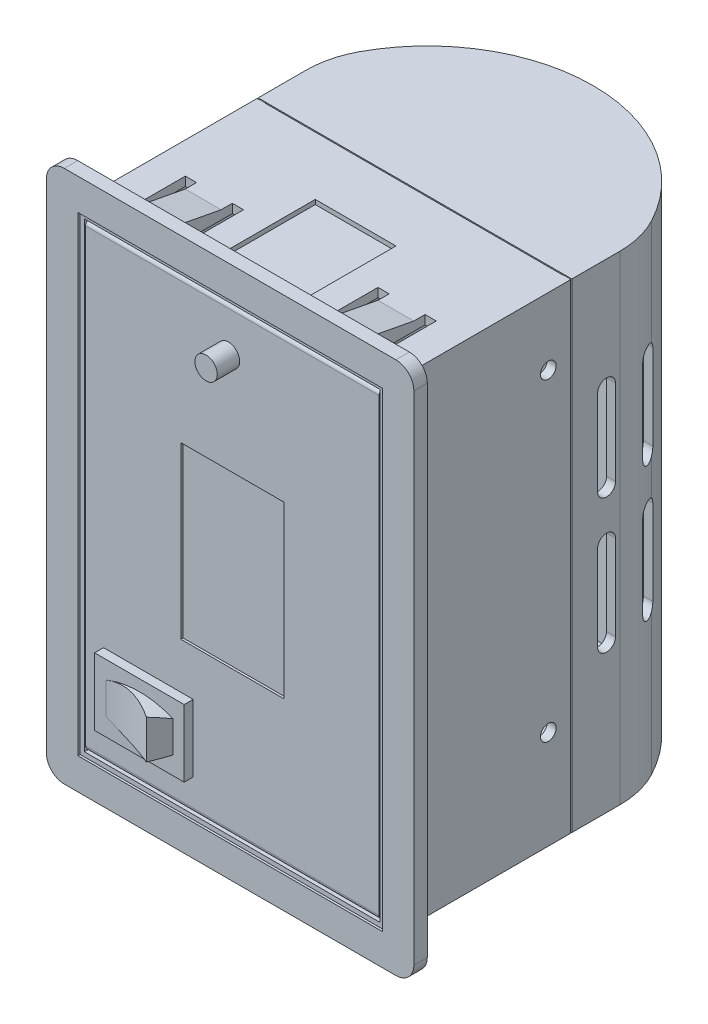
SolidWorks part; units mm, degrees
ref_plane "Спереди" through (0, 0, 0) normal (0, 0, 1) x (1, 0, 0)
ref_plane "Сверху" through (0, 0, 0) normal (0, 1, 0) x (1, 0, 0)
ref_plane "Справа" through (0, 0, 0) normal (1, 0, 0) x (0, 0, -1)
sketch "Эскиз1" plane through (0, 0, 0) normal (0, 0, 1) x (1, 0, 0)
  line L1 (-33, -51.5) -> (33, -51.5)
  line L2 (-33, -51.5) -> (-33, 51.5)
  line L3 (-33, 51.5) -> (33, 51.5)
  line L4 (33, -51.5) -> (33, 51.5)
  line L5 (-33, -51.5) -> (33, 51.5) construction
  line L6 (-33, 51.5) -> (33, -51.5) construction
  line L7 (-35, -53.5) -> (35, -53.5)
  line L8 (-35, -53.5) -> (-35, 53.5)
  line L9 (-35, 53.5) -> (35, 53.5)
  line L10 (35, -53.5) -> (35, 53.5)
  line L11 (-35, -53.5) -> (35, 53.5) construction
  line L12 (-35, 53.5) -> (35, -53.5) construction
  point P0 (0, 0)
  point P6 (0, 0)
  dimension "D1" = 2
  dimension "D2" = 2
  dimension "D3" = 107
  dimension "D4" = 70
extrude "Бобышка-Вытянуть1" add sketch "Эскиз1" along normal blind 38
sketch "Эскиз2" plane through (0, 0, 38) normal (0, 0, 1) x (1, 0, 0)
  line L1 (-37, -59.5) -> (37, -59.5)
  line L2 (-41, -55.5) -> (-41, 55.5)
  line L3 (-37, 59.5) -> (37, 59.5)
  line L4 (41, -55.5) -> (41, 55.5)
  line L5 (-41, -59.5) -> (41, 59.5) construction
  line L6 (-41, 59.5) -> (41, -59.5) construction
  line L9 (-33, -51.5) -> (33, -51.5)
  line L10 (-33, -51.5) -> (-33, 51.5)
  line L11 (-33, 51.5) -> (33, 51.5)
  line L12 (33, -51.5) -> (33, 51.5)
  line L13 (-33, -51.5) -> (33, 51.5) construction
  line L14 (-33, 51.5) -> (33, -51.5) construction
  arc A0 (-41, -55.5) -> (-37, -59.5) centre (-37, -55.5) ccw
  arc A1 (41, -55.5) -> (37, -59.5) centre (37, -55.5) cw
  arc A2 (41, 55.5) -> (37, 59.5) centre (37, 55.5) ccw
  arc A3 (-41, 55.5) -> (-37, 59.5) centre (-37, 55.5) cw
  point P0 (0, 0)
  point P6 (0, 0)
  dimension "D3" = 4
  dimension "D1" = 82
  dimension "D2" = 119
extrude "Бобышка-Вытянуть2" add sketch "Эскиз2" along normal blind 3
sketch "Эскиз3" plane through (0, 0, 41) normal (0, 0, 1) x (1, 0, 0)
  line L0 (33, -51.5) -> (33, 51.5) construction
  line L1 (-34, -52.5) -> (34, -52.5)
  line L2 (-34, -52.5) -> (-34, 52.5)
  line L3 (-34, 52.5) -> (34, 52.5)
  line L4 (34, -52.5) -> (34, 52.5)
  line L5 (-34, -52.5) -> (34, 52.5) construction
  line L6 (-34, 52.5) -> (34, -52.5) construction
  line L7 (33, 51.5) -> (-33, 51.5) construction
  point P0 (0, 0)
  dimension "D1" = 1
  dimension "D2" = 1
extrude "Вырез-Вытянуть1" cut sketch "Эскиз3" against normal blind 0.5
sketch "Эскиз4" plane through (0, 53.5, 0) normal (0, 1, 0) x (1, 0, 0)
  line L0 (37, -38) -> (-37, -38) construction
  line L1 (-9, -13) -> (9, -13)
  line L2 (-9, -13) -> (-9, -38)
  line L3 (-9, -38) -> (9, -38)
  line L4 (9, -13) -> (9, -38)
  line L5 (-9, -13) -> (9, -38) construction
  line L6 (-9, -38) -> (9, -13) construction
  point P0 (0, -25.5)
  dimension "D1" = 25
  dimension "D2" = 18
extrude "Вырез-Вытянуть2" cut sketch "Эскиз4" against normal blind 1
sketch "Эскиз5" plane through (0, 51.5, 0) normal (0, -1, 0) x (1, 0, 0)
  line L1 (33, 0) -> (-33, 0) construction
  line L2 (-10.5, 11) -> (10.5, 11)
  line L3 (-10.5, 11) -> (-10.5, 36)
  line L4 (-8.5, 38) -> (8.5, 38)
  line L5 (10.5, 11) -> (10.5, 36)
  line L6 (-10.5, 11) -> (10.5, 38) construction
  line L8 (-10.5, 38) -> (10.5, 11) construction
  arc A0 (10.5, 36) -> (8.5, 38) centre (8.5, 36) ccw
  arc A1 (-8.5, 38) -> (-10.5, 36) centre (-8.5, 36) ccw
  point P0 (0, 24.5)
  dimension "D4" = 2
  dimension "D1" = 27
  dimension "D2" = 21
  dimension "D3" = 11
extrude "Бобышка-Вытянуть3" add sketch "Эскиз5" along normal blind 1
mirror "Зеркальное отражение1" about plane through (0, 0, 0) normal (0, 1, 0) of "Бобышка-Вытянуть3", "Вырез-Вытянуть2"
sketch "Эскиз6" plane through (-35, 0, 0) normal (-1, 0, 0) x (0, 0, 1)
  line L0 (38, -53.5) -> (0, -53.5) construction
  line L1 (0, 53.5) -> (0, -53.5) construction
  line L2 (5, -31.5) -> (5, 38.5) construction
  circle A0 centre (5, -31.5) radius 1.75
  circle A1 centre (5, 38.5) radius 1.75
  dimension "D1" = 22
  dimension "D2" = 3.5
  dimension "D3" = 5
  dimension "D4" = 70
extrude "Вырез-Вытянуть3" cut sketch "Эскиз6" against normal up to surface (70 mm away) up to face at (35, 0, 19)
ref_plane "Плоскость2" through (-32.75, 0, 0) normal (1, 0, 0) x (0, 0, -1)
sketch "Эскиз9" plane through (-32.75, 0, 0) normal (1, 0, 0) x (0, 0, -1)
  line L0 (-38.5, -51.25) -> (-38.5, 51.25)
  line L1 (-38.5, 51.25) -> (-39.5, 51.25)
  line L2 (-40.5, 50.25) -> (-40.5, -50.25)
  line L3 (-39.5, -51.25) -> (-38.5, -51.25)
  line L4 (-40.5, -51.5) -> (0, -51.5) construction
  line L5 (-40.5, -51.5) -> (-40.5, 51.5) construction
  line L6 (-40.5, 51.5) -> (0, 51.5) construction
  arc A0 (-40.5, 50.25) -> (-39.5, 51.25) centre (-39.5, 50.25) cw
  arc A1 (-40.5, -50.25) -> (-39.5, -51.25) centre (-39.5, -50.25) ccw
  point P14 (-40.5, -51.25)
  dimension "D5" = 1
  dimension "D1" = 0.25
  dimension "D2" = 2
  dimension "D3" = 0
  dimension "D4" = 0.25
extrude "Бобышка-Вытянуть4" add sketch "Эскиз9" along normal blind 65.5 separate body
sketch "Эскиз10" plane through (0, 0, 40.5) normal (0, 0, 1) x (1, 0, 0)
  line L0 (-32.75, 50.25) -> (-32.75, -50.25) construction
  line L1 (-28.75, -44.25) -> (-8.75, -44.25)
  line L2 (-28.75, -44.25) -> (-28.75, -29.25)
  line L3 (-28.75, -29.25) -> (-8.75, -29.25)
  line L4 (-8.75, -44.25) -> (-8.75, -29.25)
  line L5 (32.75, -51.25) -> (-32.75, -51.25) construction
  dimension "D1" = 4
  dimension "D2" = 7
  dimension "D3" = 15
  dimension "D4" = 20
extrude "Бобышка-Вытянуть5" add sketch "Эскиз10" along normal blind 2
sketch "Эскиз11" plane through (0, 0, 42.5) normal (0, 0, 1) x (1, 0, 0)
  line L0 (-18.75, -29.25) -> (-18.75, -44.25) construction
  line L1 (-8.75, -29.25) -> (-28.75, -29.25) construction
  line L2 (-28.75, -44.25) -> (-8.75, -44.25) construction
  line L4 (-28.75, -29.25) -> (-28.75, -44.25) construction
  line L5 (-28.75, -36.75) -> (-8.75, -36.75) construction
  line L6 (-8.75, -44.25) -> (-8.75, -29.25) construction
  line L8 (-26.25, -40.25) -> (-26.25, -33.25)
  line L10 (-11.25, -40.25) -> (-11.25, -33.25)
  line L11 (-26.25, -41.75) -> (-11.25, -31.75) construction
  line L12 (-26.25, -31.75) -> (-11.25, -41.75) construction
  arc A0 (-26.25, -33.25) -> (-11.25, -33.25) centre (-18.75, -51.25) cw
  arc A1 (-26.25, -40.25) -> (-11.25, -40.25) centre (-18.75, -22.25) ccw
  point P6 (-18.75, -36.75)
  dimension "D1" = 15
  dimension "D2" = 10
  dimension "D3" = 3.5
  dimension "D4" = 3.5
  dimension "D5" = 3.5
  dimension "D6" = 3.5
extrude "Бобышка-Вытянуть6" add sketch "Эскиз11" along normal blind 3.5
sketch "Эскиз12" plane through (0, -44.25, 0) normal (0, -1, 0) x (1, 0, 0)
  line L1 (-11.25, 46) -> (-26.25, 46) construction
  line L3 (-26.25, 42.5) -> (-26.25, 46)
  line L4 (-26.25, 46) -> (-13.7007, 46)
  arc A0 (-26.25, 42.5) -> (-13.7007, 46) centre (-26.5065, 67.6673) ccw
extrude "Вырез-Вытянуть4" cut sketch "Эскиз12" against normal blind 15
sketch "Эскиз13" plane through (0, -44.25, 0) normal (0, -1, 0) x (1, 0, 0)
  line L0 (-13.7007, 46) -> (-11.25, 42.5)
  line L1 (-11.25, 42.5) -> (-11.25, 46)
  line L2 (-11.25, 46) -> (-13.7007, 46)
extrude "Вырез-Вытянуть5" cut sketch "Эскиз13" against normal blind 15
sketch "Эскиз14" plane through (0, 0, 40.5) normal (0, 0, 1) x (1, 0, 0)
  line L0 (0, 0) -> (-0.8653, 41.25) construction
  line L1 (32.75, 51.25) -> (-32.75, 51.25) construction
  circle A0 centre (-0.8653, 41.25) radius 2.5
  dimension "D2" = 5
  dimension "D1" = 10
extrude "Бобышка-Вытянуть7" add sketch "Эскиз14" along normal blind 5
sketch "Эскиз15" plane through (0, 0, 40.5) normal (0, 0, 1) x (1, 0, 0)
  line L1 (-11.5, -19) -> (11.5, -19)
  line L2 (-11.5, -19) -> (-11.5, 19)
  line L3 (-11.5, 19) -> (11.5, 19)
  line L4 (11.5, -19) -> (11.5, 19)
  line L5 (-11.5, -19) -> (11.5, 19) construction
  line L6 (-11.5, 19) -> (11.5, -19) construction
  point P0 (0, 0)
  dimension "D1" = 38
  dimension "D2" = 23
extrude "Вырез-Вытянуть6" cut sketch "Эскиз15" against normal blind 0.5
sketch "Эскиз16" plane through (0, 53.5, 0) normal (0, 1, 0) x (1, 0, 0)
  line L0 (35, 0.25) -> (35, 11)
  line L1 (-35, 0.25) -> (-35, 11)
  line L4 (35, 0) -> (-35, 0) construction
  line L5 (-35, 0.25) -> (-34.75, 0.25)
  line L6 (-34.75, 0.25) -> (-34.75, 0)
  line L7 (-34.75, 0) -> (-33.25, 0)
  line L8 (-33.25, 0) -> (-33.25, 0.25)
  line L9 (-33, 0.25) -> (-33, 10.8214)
  line L10 (-33.25, 0.25) -> (-33, 0.25)
  line L11 (34.75, 0.25) -> (34.75, 0)
  line L12 (34.75, 0) -> (33.25, 0)
  line L13 (33.25, 0) -> (33.25, 0.25)
  line L14 (33, 0.25) -> (33, 10.8214)
  line L15 (34.75, 0.25) -> (35, 0.25)
  line L16 (33, 0.25) -> (33.25, 0.25)
  arc A0 (32.6471, 20.4118) -> (-32.6471, 20.4118) centre (0, 3) ccw
  arc A1 (-30.3333, 20.7992) -> (30.3333, 20.7992) centre (0, 3.3381) cw
  arc A2 (32.6471, 20.4118) -> (35, 11) centre (15, 11) cw
  arc A3 (30.3333, 20.7992) -> (33, 10.8214) centre (13, 10.8214) cw
  arc A4 (-30.3333, 20.7992) -> (-33, 10.8214) centre (-13, 10.8214) ccw
  arc A5 (-32.6471, 20.4118) -> (-35, 11) centre (-15, 11) ccw
  point P28 (-35, 15)
  dimension "D2" = 3
  dimension "D3" = 0.25
  dimension "D11" = 20
  dimension "D4" = 0.25
  dimension "D5" = 1.5
  dimension "D6" = 2
  dimension "D7" = 15
  dimension "D8" = 0.25
  dimension "D9" = 1.5
  dimension "D10" = 2
extrude "Бобышка-Вытянуть8" add sketch "Эскиз16" against normal up to surface (107 mm away) up to face at (0, -53.5, 22.25)
sketch "Эскиз17" plane through (-34.75, 0, 0) normal (-1, 0, 0) x (0, 0, 1)
  line L0 (0, 53.5) -> (0, -53.5) construction
  line L1 (-0.25, 53.5) -> (0, 53.5)
  line L2 (-0.25, 53.5) -> (-0.25, 53.4)
  line L3 (-0.25, 53.4) -> (0, 53.4)
  line L4 (0, 53.5) -> (0, 53.4)
  line L6 (-0.25, -53.5) -> (0, -53.5)
  line L7 (-0.25, -53.5) -> (-0.25, -53.4)
  line L8 (-0.25, -53.4) -> (0, -53.4)
  line L9 (0, -53.5) -> (0, -53.4)
  dimension "D1" = 0.1
  dimension "D2" = 0.1
extrude "Вырез-Вытянуть8" cut sketch "Эскиз17" against normal up to surface (69.5 mm away) up to face at (34.75, 0, -0.125)
sketch "Эскиз18" plane through (0, -53.5, 0) normal (0, -1, 0) x (1, 0, 0)
  line L0 (-33, -0.25) -> (-33, -10.8214)
  line L1 (33, -10.8214) -> (33, -0.25)
  line L2 (33, -0.25) -> (-33, -0.25)
  arc A0 (-33, -10.8214) -> (-30.3333, -20.7992) centre (-13, -10.8214) ccw
  arc A1 (30.3333, -20.7992) -> (33, -10.8214) centre (13, -10.8214) ccw
  arc A2 (-30.3333, -20.7992) -> (30.3333, -20.7992) centre (0, -3.3381) ccw
extrude "Бобышка-Вытянуть9" add sketch "Эскиз18" against normal blind 2
mirror "Зеркальное отражение2" about plane through (0, 0, 0) normal (0, 1, 0) of "Бобышка-Вытянуть9"
sketch "Эскиз19" plane through (0, 53.5, 0) normal (0, 1, 0) x (1, 0, 0)
  line L0 (-9, -38) -> (-35, -38) construction
  line L1 (-28, -38) -> (-15, -38)
  line L2 (-28, -38) -> (-28, -23)
  line L3 (-28, -23) -> (-15, -23)
  line L4 (-15, -38) -> (-15, -23)
  line L5 (35, -38) -> (9, -38) construction
  line L6 (15, -38) -> (28, -38)
  line L7 (15, -38) -> (15, -23)
  line L8 (15, -23) -> (28, -23)
  line L9 (28, -38) -> (28, -23)
  line L10 (9, -38) -> (9, -13) construction
  line L11 (-9, -13) -> (-9, -38) construction
  dimension "D1" = 13
  dimension "D2" = 15
  dimension "D3" = 6
  dimension "D4" = 6
extrude "Вырез-Вытянуть9" cut sketch "Эскиз19" against normal blind 2
ref_plane "Плоскость3" through (-17.5, 0, 0) normal (-1, 0, 0) x (0, 0, 1)
sketch "Эскиз20" plane through (-17.5, 0, 0) normal (-1, 0, 0) x (0, 0, 1)
  line L0 (23, 53.5) -> (23, 51.5)
  line L1 (23, 51.5) -> (23, 53.5) construction
  line L2 (23, 53.5) -> (25.5, 53.5)
  line L3 (25.5, 53.5) -> (35.5, 55.4064)
  line L4 (35.5, 55.4064) -> (37.5, 53.5)
  line L5 (38, 53.5) -> (0, 53.5) construction
  line L6 (38, 55.5) -> (38, -55.5) construction
  line L7 (37.5, 53.5) -> (37.5, 51.5)
  line L8 (37.5, 51.5) -> (23, 51.5)
  dimension "D1" = 2
  dimension "D2" = 0
  dimension "D3" = 10
  dimension "D4" = 2.5
  dimension "D5" = 0.5
extrude "Бобышка-Вытянуть10" add sketch "Эскиз20" along normal blind 8
pattern_linear "Линейный массив1" count 2 spacing 43 along (1, 0, 0) of "Бобышка-Вытянуть10"
mirror "Зеркальное отражение3" about plane through (0, 0, 0) normal (0, 1, 0) of "Вырез-Вытянуть9", "Бобышка-Вытянуть10", "Линейный массив1"
sketch "Эскиз21" plane through (-35, 0, 0) normal (-1, 0, 0) x (0, 0, 1)
  line L0 (-8, 28.5) -> (-8, 9.5) construction
  line L1 (-6, 28.5) -> (-6, 9.5)
  line L2 (-10, 28.5) -> (-10, 9.5)
  line L3 (-8, -1.5) -> (-8, -20.5) construction
  line L4 (-6, -1.5) -> (-6, -20.5)
  line L5 (-10, -1.5) -> (-10, -20.5)
  line L6 (-0.25, -53.5) -> (-11, -53.5) construction
  line L7 (0, 53.5) -> (0, -53.5) construction
  arc A0 (-6, 28.5) -> (-10, 28.5) centre (-8, 28.5) ccw
  arc A1 (-10, 9.5) -> (-6, 9.5) centre (-8, 9.5) ccw
  arc A2 (-6, -1.5) -> (-10, -1.5) centre (-8, -1.5) ccw
  arc A3 (-10, -20.5) -> (-6, -20.5) centre (-8, -20.5) ccw
  point P2 (-8, 19)
  point P7 (-8, -11)
  dimension "D1" = 4
  dimension "D2" = 19
  dimension "D3" = 33
  dimension "D4" = 30
  dimension "D5" = 8
extrude "Вырез-Вытянуть10" cut sketch "Эскиз21" against normal up to surface (70 mm away) up to face at (35, 0, -5.625)
pattern_linear "Линейный массив2" count 2 spacing 11 along (0, 0, -1) of "Вырез-Вытянуть10"
sketch "Эскиз22" plane through (0, -53.5, 0) normal (0, -1, 0) x (1, 0, 0)
  line L0 (-35, 0) -> (35, 0) construction
  circle A0 centre (21.5, 16.5) radius 2.5
  circle A1 centre (21.5, 6.5) radius 2.5
  dimension "D1" = 5
  dimension "D2" = 10
  dimension "D3" = 6.5
extrude "Вырез-Вытянуть11" cut sketch "Эскиз22" against normal blind 2
